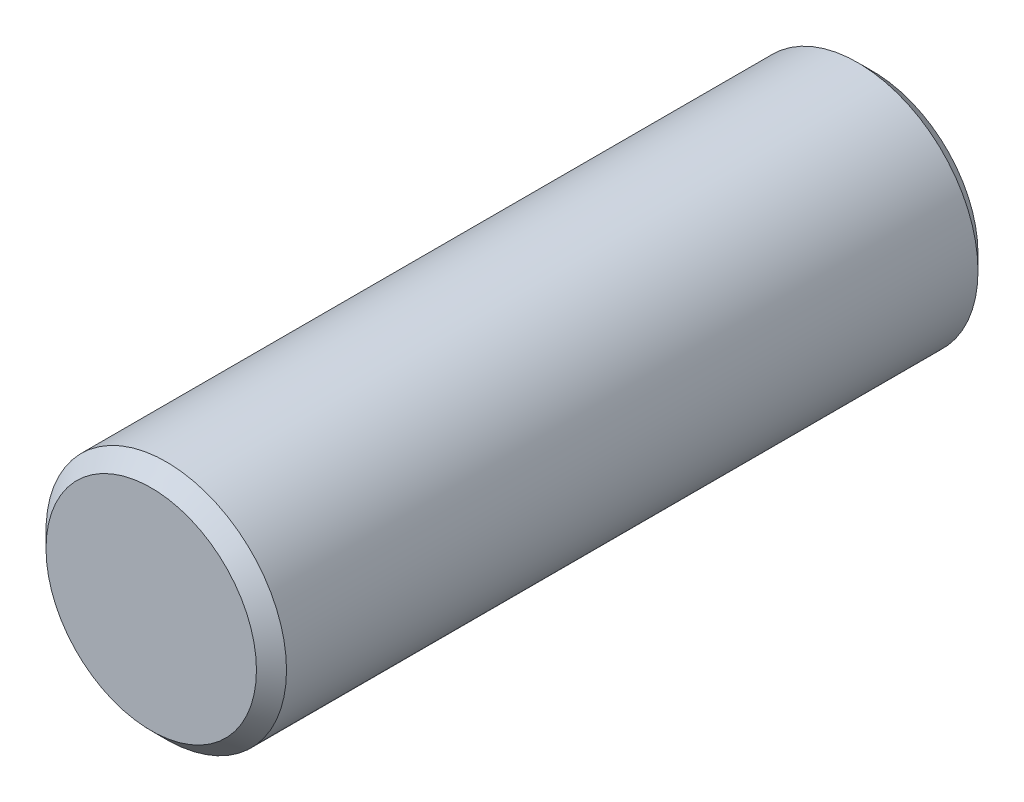
SolidWorks part; units mm, degrees
ref_plane "Front Plane" through (0, 0, 0) normal (0, 0, 1) x (1, 0, 0)
ref_plane "Top Plane" through (0, 0, 0) normal (0, 1, 0) x (1, 0, 0)
ref_plane "Right Plane" through (0, 0, 0) normal (1, 0, 0) x (0, 0, -1)
sketch "Sketch1" plane through (0, 0, 0) normal (0, 1, 0) x (1, 0, 0)
  line L0 (1.75, 6) -> (0, 6)
  line L1 (0, 6) -> (0, -6)
  line L2 (0, -6) -> (1.75, -6)
  line L3 (1.75, -6) -> (2, -5.75)
  line L4 (2, -5.75) -> (2, 5.75)
  line L5 (2, 5.75) -> (1.75, 6)
  line L6 (0, 6) -> (0, -6) construction
revolve "Revolve1" add sketch "Sketch1" angle 360 about L6
